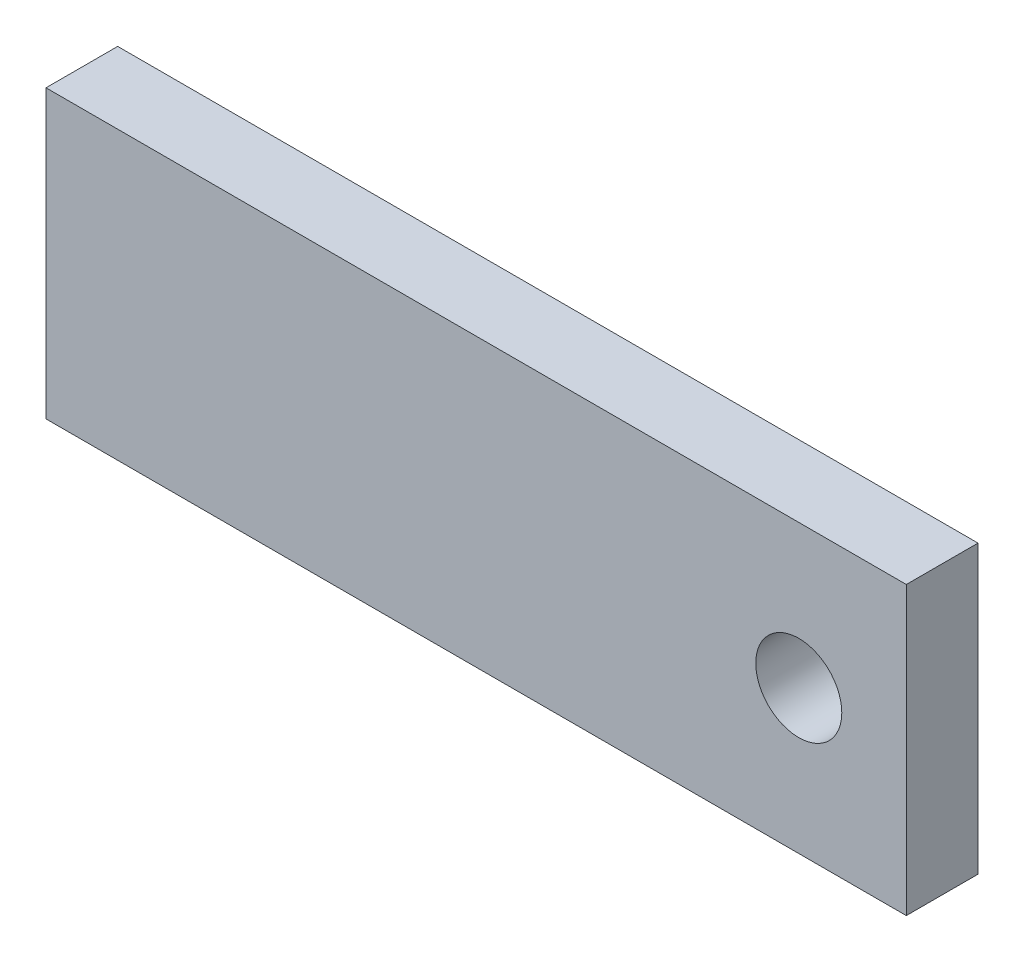
SolidWorks part; units mm, degrees
ref_plane "前视基准面" through (0, 0, 0) normal (0, 0, 1) x (1, 0, 0)
ref_plane "上视基准面" through (0, 0, 0) normal (0, 1, 0) x (1, 0, 0)
ref_plane "右视基准面" through (0, 0, 0) normal (1, 0, 0) x (0, 0, -1)
sketch "草图2" plane through (0, 0, 0) normal (0, 0, 1) x (1, 0, 0)
  line L1 (0, 20) -> (120, 20)
  line L2 (0, 20) -> (0, -20)
  line L3 (0, -20) -> (120, -20)
  line L4 (120, 20) -> (120, -20)
extrude "凸台-拉伸1" add sketch "草图2" along normal blind 10
sketch "草图3" plane through (0, 0, 10) normal (0, 0, 1) x (1, 0, 0)
  circle A0 centre (105, 0) radius 6
extrude "切除-拉伸1" cut sketch "草图3" against normal through all
